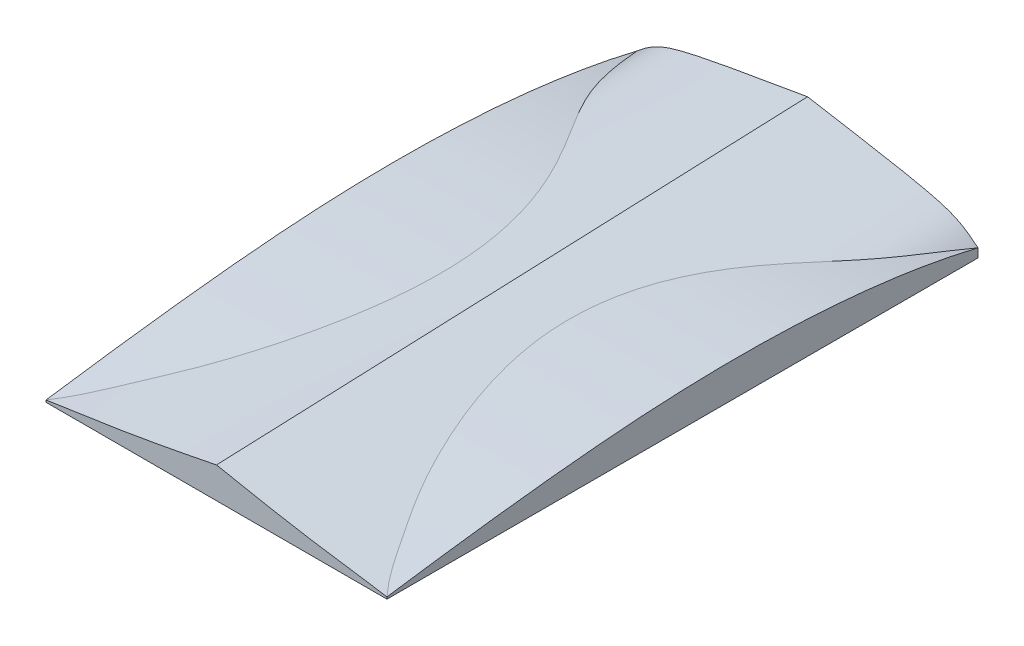
SolidWorks part; units mm, degrees
material "Custom Plastic"
ref_plane "Front Plane" through (0, 0, 0) normal (0, 0, 1) x (1, 0, 0)
ref_plane "Top Plane" through (0, 0, 0) normal (0, 1, 0) x (1, 0, 0)
ref_plane "Right Plane" through (0, 0, 0) normal (1, 0, 0) x (0, 0, -1)
sketch "Sketch1" plane through (0, 0, 0) normal (0, 1, 0) x (1, 0, 0)
  line L1 (37.5, -65) -> (-37.5, -65)
  line L2 (37.5, -65) -> (37.5, 65)
  line L3 (37.5, 65) -> (-37.5, 65)
  line L4 (-37.5, -65) -> (-37.5, 65)
  line L5 (37.5, -65) -> (-37.5, 65) construction
  line L6 (37.5, 65) -> (-37.5, -65) construction
  point P0 (0, 0)
  dimension "D1" = 130
  dimension "D2" = 75
extrude "Boss-Extrude1" add sketch "Sketch1" along normal mid plane 20
sketch "Sketch4" plane through (0, 0, 65) normal (0, 0, 1) x (1, 0, 0)
  line L3 (-37.5, -10) -> (37.5, -10)
  line L4 (-37.5, -9.5528) -> (-37.5, -10)
  line L5 (37.5, -10) -> (37.5, -9.5528)
  line L6 (-37.5, -10) -> (37.5, -10)
  line L7 (-37.5, -9.5528) -> (-37.5, -10)
  line L8 (37.5, -10) -> (37.5, -9.5528)
  spline S2 degree 3 poles (1362.5277, -2586.3983) (529.3557, 276.2334) (276.2831, 48.9391) (-12.45, -5.5894) (-15.5687, -6.1588) (-20.2581, -6.9528) (-21.823, -7.2062) (-24.9574, -7.6822) (-26.5273, -7.902) (-29.6645, -8.3595) (-31.231, -8.602) (-143.085, -25.9114) (-260.3256, 2.6626) (83.6689, -2996.3053) knots -22.671348 -22.671348 -22.671348 -22.671348 0.25 0.25 0.5 0.5 0.625 0.625 0.75 0.75 0.875 0.875 9.675339 9.675339 9.675339 9.675339 only from (0, -3.1785) to (-37.5, -9.5528)
  spline S3 degree 3 poles (-83.6298, -2996.3455) (260.326, 2.663) (143.0854, -25.9115) (31.231, -8.602) (29.6645, -8.3595) (26.5273, -7.902) (24.9573, -7.6822) (21.823, -7.2062) (20.2581, -6.9528) (15.5687, -6.1588) (12.45, -5.5894) (-276.2862, 48.9397) (-529.3639, 276.2389) (-1362.51, -2586.49) knots -8.675371 -8.675371 -8.675371 -8.675371 0.125 0.125 0.25 0.25 0.375 0.375 0.5 0.5 0.75 0.75 23.671611 23.671611 23.671611 23.671611 only from (37.5, -9.5528) to (0, -3.1785)
  spline S4 degree 3 poles (0, -3.1785) (-3.1082, -3.8038) (-6.2196, -4.4128) (-12.45, -5.5894) (-15.5687, -6.1588) (-20.2581, -6.9528) (-21.823, -7.2062) (-24.9574, -7.6822) (-26.5273, -7.902) (-29.6645, -8.3595) (-31.231, -8.602) (-34.3641, -9.0868) (-35.932, -9.32) (-37.5, -9.5528) knots 0 0 0 0 0.25 0.25 0.5 0.5 0.625 0.625 0.75 0.75 0.875 0.875 1 1 1 1
  spline S5 degree 3 poles (37.5, -9.5528) (35.932, -9.32) (34.3641, -9.0868) (31.231, -8.602) (29.6645, -8.3595) (26.5273, -7.902) (24.9573, -7.6822) (21.823, -7.2062) (20.2581, -6.9528) (15.5687, -6.1588) (12.45, -5.5894) (6.2196, -4.4128) (3.1082, -3.8038) (0, -3.1785) knots 0 0 0 0 0.125 0.125 0.25 0.25 0.375 0.375 0.5 0.5 0.75 0.75 1 1 1 1
  dimension "D1" = 0
sketch "Sketch7" plane through (0, 0, -65) normal (0, 0, -1) x (-1, 0, 0)
  line L3 (-37.5, -10) -> (37.5, -10)
  line L4 (-37.5, -8.0672) -> (-37.5, -10)
  line L5 (37.5, -10) -> (37.5, -8.0672)
  line L6 (-37.5, -10) -> (37.5, -10)
  line L7 (-37.5, -8.0672) -> (-37.5, -10)
  line L8 (37.5, -10) -> (37.5, -8.0672)
  spline S2 degree 3 poles (147.4318, 2953.7815) (446.6651, 32.4517) (214.3649, 39.1733) (-12.8775, -0.2551) (-16.0948, -0.8201) (-20.91, -1.727) (-22.5132, -2.0391) (-24.911, -2.5465) (-25.7095, -2.7224) (-27.2981, -3.0969) (-28.0886, -3.2952) (-29.6554, -3.7331) (-30.4316, -3.9729) (-31.958, -4.5286) (-32.7073, -4.8469) (-33.8, -5.4157) (-34.1598, -5.6214) (-34.8648, -6.0606) (-35.208, -6.2927) (-65.0007, -27.7231) (-40.8384, -121.4893) (-1903.7188, 2339.0086) knots -17.151311 -17.151311 -17.151311 -17.151311 0.25 0.25 0.5 0.5 0.625 0.625 0.6875 0.6875 0.75 0.75 0.8125 0.8125 0.875 0.875 0.90625 0.90625 0.9375 0.9375 3.676306 3.676306 3.676306 3.676306 only from (0, 1.9592) to (-37.5, -8.0672)
  spline S3 degree 3 poles (1650.2449, 2519.9794) (48.7593, -126.412) (64.9758, -27.7798) (34.915, -6.0803) (34.232, -5.6461) (32.7996, -4.8901) (32.0515, -4.5662) (30.8943, -4.1398) (30.5026, -4.0071) (29.718, -3.7579) (29.3242, -3.6412) (28.1393, -3.3083) (27.345, -3.1085) (25.7519, -2.732) (24.953, -2.5557) (22.5524, -2.0469) (20.9467, -1.7341) (16.124, -0.8253) (12.901, -0.2592) (-214.5163, 39.2022) (-447.698, 32.4578) (-103.9777, 2955.3101) knots -2.727115 -2.727115 -2.727115 -2.727115 0.0625 0.0625 0.125 0.125 0.1875 0.1875 0.21875 0.21875 0.25 0.25 0.3125 0.3125 0.375 0.375 0.5 0.5 0.75 0.75 18.133105 18.133105 18.133105 18.133105 only from (37.5, -8.0672) to (0, 1.9592)
  spline S4 degree 3 poles (0, 1.9592) (-3.2203, 1.4108) (-6.4405, 0.8618) (-12.8775, -0.2551) (-16.0948, -0.8201) (-20.91, -1.727) (-22.5132, -2.0391) (-24.911, -2.5465) (-25.7095, -2.7224) (-27.2981, -3.0969) (-28.0886, -3.2952) (-29.6554, -3.7331) (-30.4316, -3.9729) (-31.958, -4.5286) (-32.7073, -4.8469) (-33.8, -5.4157) (-34.1598, -5.6214) (-34.8648, -6.0606) (-35.208, -6.2927) (-36.2163, -7.018) (-36.8606, -7.5393) (-37.5, -8.0672) knots 0 0 0 0 0.25 0.25 0.5 0.5 0.625 0.625 0.6875 0.6875 0.75 0.75 0.8125 0.8125 0.875 0.875 0.90625 0.90625 0.9375 0.9375 1 1 1 1
  spline S5 degree 3 poles (37.5, -8.0672) (36.8684, -7.5457) (36.2325, -7.0314) (34.915, -6.0803) (34.232, -5.6461) (32.7996, -4.8901) (32.0515, -4.5662) (30.8943, -4.1398) (30.5026, -4.0071) (29.718, -3.7579) (29.3242, -3.6412) (28.1393, -3.3083) (27.345, -3.1085) (25.7519, -2.732) (24.953, -2.5557) (22.5524, -2.0469) (20.9467, -1.7341) (16.124, -0.8253) (12.901, -0.2592) (6.4524, 0.8598) (3.2263, 1.4098) (0, 1.9592) knots 0 0 0 0 0.0625 0.0625 0.125 0.125 0.1875 0.1875 0.21875 0.21875 0.25 0.25 0.3125 0.3125 0.375 0.375 0.5 0.5 0.75 0.75 1 1 1 1
  dimension "D1" = 0
sketch "Sketch8" plane through (0, 0, 65) normal (0, 0, 1) x (1, 0, 0)
  line L0 (37.5, -10) -> (37.5, -9.5528) construction
  line L1 (-37.5, -9.5528) -> (-37.5, -10) construction
  line L2 (-37.5, -10) -> (37.5, -10) construction
  line L3 (37.5, -10) -> (37.5, -9.5528)
  line L4 (-37.5, -9.5528) -> (-37.5, -10)
  line L5 (-37.5, -10) -> (37.5, -10)
  line L10 (-37.5, -10) -> (37.5, -10)
  line L11 (37.5, -10) -> (37.5, 10)
  line L12 (37.5, 10) -> (-37.5, 10)
  line L13 (-37.5, 10) -> (-37.5, -10)
  line L14 (-37.5, -10) -> (37.5, -10)
  line L15 (37.5, -10) -> (37.5, 10)
  line L16 (37.5, 10) -> (-37.5, 10)
  line L17 (-37.5, 10) -> (-37.5, -10)
  spline S0 degree 3 poles (25.1955, -2002.3309) (230.9447, -3.8028) (129.2143, -23.7649) (31.231, -8.602) (29.6645, -8.3595) (26.5273, -7.902) (24.9573, -7.6822) (21.823, -7.2062) (20.2581, -6.9528) (15.5687, -6.1588) (12.45, -5.5894) (-239.6477, 42.0203) (-463.9005, 220.7771) (-1069.2322, -1630.4759) knots -7.568527 -7.568527 -7.568527 -7.568527 0.125 0.125 0.25 0.25 0.375 0.375 0.5 0.5 0.75 0.75 20.731303 20.731303 20.731303 20.731303 only from (37.5, -9.5528) to (0, -3.1785) construction
  spline S1 degree 3 poles (1069.2512, -1630.4468) (463.8959, 220.7748) (239.6463, 42.0201) (-12.45, -5.5894) (-15.5687, -6.1588) (-20.2581, -6.9528) (-21.823, -7.2062) (-24.9574, -7.6822) (-26.5273, -7.902) (-29.6645, -8.3595) (-31.231, -8.602) (-129.2137, -23.7648) (-230.9439, -3.8031) (-25.1705, -2002.2918) knots -19.731182 -19.731182 -19.731182 -19.731182 0.25 0.25 0.5 0.5 0.625 0.625 0.75 0.75 0.875 0.875 8.568483 8.568483 8.568483 8.568483 only from (0, -3.1785) to (-37.5, -9.5528) construction
  spline S2 degree 3 poles (37.5, -9.5528) (35.932, -9.32) (34.3641, -9.0868) (31.231, -8.602) (29.6645, -8.3595) (26.5273, -7.902) (24.9573, -7.6822) (21.823, -7.2062) (20.2581, -6.9528) (15.5687, -6.1588) (12.45, -5.5894) (6.2196, -4.4128) (3.1082, -3.8038) (0, -3.1785) knots 0 0 0 0 0.125 0.125 0.25 0.25 0.375 0.375 0.5 0.5 0.75 0.75 1 1 1 1
  spline S3 degree 3 poles (0, -3.1785) (-3.1082, -3.8038) (-6.2196, -4.4128) (-12.45, -5.5894) (-15.5687, -6.1588) (-20.2581, -6.9528) (-21.823, -7.2062) (-24.9574, -7.6822) (-26.5273, -7.902) (-29.6645, -8.3595) (-31.231, -8.602) (-34.3641, -9.0868) (-35.932, -9.32) (-37.5, -9.5528) knots 0 0 0 0 0.25 0.25 0.5 0.5 0.625 0.625 0.75 0.75 0.875 0.875 1 1 1 1
  dimension "D1" = 0
sketch "Sketch14" plane through (37.5, 0, 0) normal (1, 0, 0) x (0, 0, -1)
  line L4 (-65, -10) -> (65, -10)
  line L5 (65, -10) -> (65, 10)
  line L6 (65, 10) -> (-65, 10)
  line L7 (-65, 10) -> (-65, -10)
  line L8 (-65, -10) -> (65, -10)
  line L9 (65, -10) -> (65, 10)
  line L10 (65, 10) -> (-65, 10)
  line L11 (-65, 10) -> (-65, -10)
  spline S0 degree 3 poles (302.1115, -1979.9432) (336.8552, -226.6773) (202.4863, -27.6201) (43.5369, -4.1805) (38.1282, -3.6036) (27.2724, -2.8022) (21.8255, -2.5767) (13.6304, -2.4646) (10.8947, -2.4652) (5.4345, -2.5372) (2.7076, -2.6082) (-5.4642, -2.9203) (-10.8999, -3.2637) (-21.7529, -4.155) (-27.1705, -4.699) (-37.9947, -5.9114) (-43.4009, -6.5821) (-337.0021, -45.3581) (-614.0336, -207.5109) (-1071.7834, 1638.4672) knots -3.439572 -3.439572 -3.439572 -3.439572 0.125 0.125 0.25 0.25 0.375 0.375 0.4375 0.4375 0.5 0.5 0.625 0.625 0.75 0.75 0.875 0.875 7.543306 7.543306 7.543306 7.543306 only from (65, -8.0672) to (-65, -9.5528) construction
  spline S1 degree 3 poles (65, -8.0672) (59.6686, -6.7798) (54.3071, -5.7688) (43.5369, -4.1805) (38.1282, -3.6036) (27.2724, -2.8022) (21.8255, -2.5767) (13.6304, -2.4646) (10.8947, -2.4652) (5.4345, -2.5372) (2.7076, -2.6082) (-5.4642, -2.9203) (-10.8999, -3.2637) (-21.7529, -4.155) (-27.1705, -4.699) (-37.9947, -5.9114) (-43.4009, -6.5821) (-54.2057, -8.0091) (-59.6042, -8.7662) (-65, -9.5528) knots 0 0 0 0 0.125 0.125 0.25 0.25 0.375 0.375 0.4375 0.4375 0.5 0.5 0.625 0.625 0.75 0.75 0.875 0.875 1 1 1 1
  dimension "D1" = 0
sketch "Sketch15" plane through (-37.5, 0, 0) normal (-1, 0, 0) x (0, 0, 1)
  line L0 (65, -10) -> (-65, -10) construction
  line L1 (65, -10) -> (-65, -10)
  line L2 (-65, -8.0672) -> (-65, -10)
  line L3 (65, -9.5528) -> (65, -10)
  spline S0 degree 3 poles (-302.1115, -1979.9432) (-336.8552, -226.6773) (-202.4863, -27.6201) (-43.5369, -4.1805) (-38.1282, -3.6036) (-27.2724, -2.8022) (-21.8255, -2.5767) (-13.6304, -2.4646) (-10.8947, -2.4652) (-5.4345, -2.5372) (-2.7076, -2.6082) (5.4642, -2.9203) (10.8999, -3.2637) (21.7529, -4.155) (27.1705, -4.699) (37.9947, -5.9114) (43.4009, -6.5821) (337.0021, -45.3581) (614.0336, -207.5109) (1071.7834, 1638.4672) knots -3.439572 -3.439572 -3.439572 -3.439572 0.125 0.125 0.25 0.25 0.375 0.375 0.4375 0.4375 0.5 0.5 0.625 0.625 0.75 0.75 0.875 0.875 7.543306 7.543306 7.543306 7.543306 only from (-65, -8.0672) to (65, -9.5528) construction
  spline S1 degree 3 poles (-65, -8.0672) (-59.6686, -6.7798) (-54.3071, -5.7688) (-43.5369, -4.1805) (-38.1282, -3.6036) (-27.2724, -2.8022) (-21.8255, -2.5767) (-13.6304, -2.4646) (-10.8947, -2.4652) (-5.4345, -2.5372) (-2.7076, -2.6082) (5.4642, -2.9203) (10.8999, -3.2637) (21.7529, -4.155) (27.1705, -4.699) (37.9947, -5.9114) (43.4009, -6.5821) (54.2057, -8.0091) (59.6042, -8.7662) (65, -9.5528) knots 0 0 0 0 0.125 0.125 0.25 0.25 0.375 0.375 0.4375 0.4375 0.5 0.5 0.625 0.625 0.75 0.75 0.875 0.875 1 1 1 1
sketch "Sketch16" plane through (37.5, 0, 0) normal (1, 0, 0) x (0, 0, -1)
  line L0 (-65, -10) -> (65, -10) construction
  line L1 (-65, -10) -> (65, -10)
  line L2 (-65, -9.5528) -> (-65, -10)
  line L3 (65, -8.0672) -> (65, -10)
  spline S0 degree 3 poles (302.1115, -1979.9432) (336.8552, -226.6773) (202.4863, -27.6201) (43.5369, -4.1805) (38.1282, -3.6036) (27.2724, -2.8022) (21.8255, -2.5767) (13.6304, -2.4646) (10.8947, -2.4652) (5.4345, -2.5372) (2.7076, -2.6082) (-5.4642, -2.9203) (-10.8999, -3.2637) (-21.7529, -4.155) (-27.1705, -4.699) (-37.9947, -5.9114) (-43.4009, -6.5821) (-337.0021, -45.3581) (-614.0336, -207.5109) (-1071.7834, 1638.4672) knots -3.439572 -3.439572 -3.439572 -3.439572 0.125 0.125 0.25 0.25 0.375 0.375 0.4375 0.4375 0.5 0.5 0.625 0.625 0.75 0.75 0.875 0.875 7.543306 7.543306 7.543306 7.543306 only from (65, -8.0672) to (-65, -9.5528) construction
  spline S1 degree 3 poles (65, -8.0672) (59.6686, -6.7798) (54.3071, -5.7688) (43.5369, -4.1805) (38.1282, -3.6036) (27.2724, -2.8022) (21.8255, -2.5767) (13.6304, -2.4646) (10.8947, -2.4652) (5.4345, -2.5372) (2.7076, -2.6082) (-5.4642, -2.9203) (-10.8999, -3.2637) (-21.7529, -4.155) (-27.1705, -4.699) (-37.9947, -5.9114) (-43.4009, -6.5821) (-54.2057, -8.0091) (-59.6042, -8.7662) (-65, -9.5528) knots 0 0 0 0 0.125 0.125 0.25 0.25 0.375 0.375 0.4375 0.4375 0.5 0.5 0.625 0.625 0.75 0.75 0.875 0.875 1 1 1 1
sketch "Sketch17" plane through (0, 0, -65) normal (0, 0, -1) x (-1, 0, 0)
  line L0 (37.5, -10) -> (37.5, -8.0672) construction
  line L1 (-37.5, -10) -> (37.5, -10) construction
  line L2 (-37.5, -8.0672) -> (-37.5, -10) construction
  line L3 (37.5, -10) -> (37.5, -8.0672)
  line L4 (-37.5, -10) -> (37.5, -10)
  line L5 (-37.5, -8.0672) -> (-37.5, -10)
  spline S0 degree 3 poles (1131.1538, 1665.3044) (52.0496, -103.3935) (61.3715, -25.178) (34.915, -6.0803) (34.232, -5.6461) (32.7996, -4.8901) (32.0515, -4.5662) (30.8943, -4.1398) (30.5026, -4.0071) (29.718, -3.7579) (29.3242, -3.6412) (28.1393, -3.3083) (27.345, -3.1085) (25.7519, -2.732) (24.953, -2.5557) (22.5524, -2.0469) (20.9467, -1.7341) (16.124, -0.8253) (12.901, -0.2592) (-185.493, 34.1661) (-387.4749, 33.439) (-209.7345, 1960.999) knots -2.38515 -2.38515 -2.38515 -2.38515 0.0625 0.0625 0.125 0.125 0.1875 0.1875 0.21875 0.21875 0.25 0.25 0.3125 0.3125 0.375 0.375 0.5 0.5 0.75 0.75 15.882747 15.882747 15.882747 15.882747 only from (37.5, -8.0672) to (0, 1.9592) construction
  spline S1 degree 3 poles (238.2487, 1957.9567) (386.5167, 33.4284) (185.295, 34.1294) (-12.8775, -0.2551) (-16.0948, -0.8201) (-20.91, -1.727) (-22.5132, -2.0391) (-24.911, -2.5465) (-25.7095, -2.7224) (-27.2981, -3.0969) (-28.0886, -3.2952) (-29.6554, -3.7331) (-30.4316, -3.9729) (-31.958, -4.5286) (-32.7073, -4.8469) (-33.8, -5.4157) (-34.1598, -5.6214) (-34.8648, -6.0606) (-35.208, -6.2927) (-61.381, -25.1194) (-45.9671, -99.5405) (-1298.8469, 1542.7761) knots -14.893272 -14.893272 -14.893272 -14.893272 0.25 0.25 0.5 0.5 0.625 0.625 0.6875 0.6875 0.75 0.75 0.8125 0.8125 0.875 0.875 0.90625 0.90625 0.9375 0.9375 3.339749 3.339749 3.339749 3.339749 only from (0, 1.9592) to (-37.5, -8.0672) construction
  spline S2 degree 3 poles (37.5, -8.0672) (36.8684, -7.5457) (36.2325, -7.0314) (34.915, -6.0803) (34.232, -5.6461) (32.7996, -4.8901) (32.0515, -4.5662) (30.8943, -4.1398) (30.5026, -4.0071) (29.718, -3.7579) (29.3242, -3.6412) (28.1393, -3.3083) (27.345, -3.1085) (25.7519, -2.732) (24.953, -2.5557) (22.5524, -2.0469) (20.9467, -1.7341) (16.124, -0.8253) (12.901, -0.2592) (6.4524, 0.8598) (3.2263, 1.4098) (0, 1.9592) knots 0 0 0 0 0.0625 0.0625 0.125 0.125 0.1875 0.1875 0.21875 0.21875 0.25 0.25 0.3125 0.3125 0.375 0.375 0.5 0.5 0.75 0.75 1 1 1 1
  spline S3 degree 3 poles (0, 1.9592) (-3.2203, 1.4108) (-6.4405, 0.8618) (-12.8775, -0.2551) (-16.0948, -0.8201) (-20.91, -1.727) (-22.5132, -2.0391) (-24.911, -2.5465) (-25.7095, -2.7224) (-27.2981, -3.0969) (-28.0886, -3.2952) (-29.6554, -3.7331) (-30.4316, -3.9729) (-31.958, -4.5286) (-32.7073, -4.8469) (-33.8, -5.4157) (-34.1598, -5.6214) (-34.8648, -6.0606) (-35.208, -6.2927) (-36.2163, -7.018) (-36.8606, -7.5393) (-37.5, -8.0672) knots 0 0 0 0 0.25 0.25 0.5 0.5 0.625 0.625 0.6875 0.6875 0.75 0.75 0.8125 0.8125 0.875 0.875 0.90625 0.90625 0.9375 0.9375 1 1 1 1
sketch "Sketch18" plane through (0, 0, -65) normal (0, 0, -1) x (-1, 0, 0)
  line L0 (-37.5, -8.0672) -> (-37.5, 10)
  line L1 (-37.5, 10) -> (37.5, 10)
  line L2 (37.5, 10) -> (37.5, -8.0672)
  spline S0 degree 3 poles (1131.1538, 1665.3044) (52.0496, -103.3935) (61.3715, -25.178) (34.915, -6.0803) (34.232, -5.6461) (32.7996, -4.8901) (32.0515, -4.5662) (30.8943, -4.1398) (30.5026, -4.0071) (29.718, -3.7579) (29.3242, -3.6412) (28.1393, -3.3083) (27.345, -3.1085) (25.7519, -2.732) (24.953, -2.5557) (22.5524, -2.0469) (20.9467, -1.7341) (16.124, -0.8253) (12.901, -0.2592) (-185.493, 34.1661) (-387.4749, 33.439) (-209.7345, 1960.999) knots -2.38515 -2.38515 -2.38515 -2.38515 0.0625 0.0625 0.125 0.125 0.1875 0.1875 0.21875 0.21875 0.25 0.25 0.3125 0.3125 0.375 0.375 0.5 0.5 0.75 0.75 15.882747 15.882747 15.882747 15.882747 only from (37.5, -8.0672) to (0, 1.9592) construction
  spline S1 degree 3 poles (238.2487, 1957.9567) (386.5167, 33.4284) (185.295, 34.1294) (-12.8775, -0.2551) (-16.0948, -0.8201) (-20.91, -1.727) (-22.5132, -2.0391) (-24.911, -2.5465) (-25.7095, -2.7224) (-27.2981, -3.0969) (-28.0886, -3.2952) (-29.6554, -3.7331) (-30.4316, -3.9729) (-31.958, -4.5286) (-32.7073, -4.8469) (-33.8, -5.4157) (-34.1598, -5.6214) (-34.8648, -6.0606) (-35.208, -6.2927) (-61.381, -25.1194) (-45.9671, -99.5405) (-1298.8469, 1542.7761) knots -14.893272 -14.893272 -14.893272 -14.893272 0.25 0.25 0.5 0.5 0.625 0.625 0.6875 0.6875 0.75 0.75 0.8125 0.8125 0.875 0.875 0.90625 0.90625 0.9375 0.9375 3.339749 3.339749 3.339749 3.339749 only from (0, 1.9592) to (-37.5, -8.0672) construction
  spline S2 degree 3 poles (37.5, -8.0672) (36.8684, -7.5457) (36.2325, -7.0314) (34.915, -6.0803) (34.232, -5.6461) (32.7996, -4.8901) (32.0515, -4.5662) (30.8943, -4.1398) (30.5026, -4.0071) (29.718, -3.7579) (29.3242, -3.6412) (28.1393, -3.3083) (27.345, -3.1085) (25.7519, -2.732) (24.953, -2.5557) (22.5524, -2.0469) (20.9467, -1.7341) (16.124, -0.8253) (12.901, -0.2592) (6.4524, 0.8598) (3.2263, 1.4098) (0, 1.9592) knots 0 0 0 0 0.0625 0.0625 0.125 0.125 0.1875 0.1875 0.21875 0.21875 0.25 0.25 0.3125 0.3125 0.375 0.375 0.5 0.5 0.75 0.75 1 1 1 1
  spline S3 degree 3 poles (0, 1.9592) (-3.2203, 1.4108) (-6.4405, 0.8618) (-12.8775, -0.2551) (-16.0948, -0.8201) (-20.91, -1.727) (-22.5132, -2.0391) (-24.911, -2.5465) (-25.7095, -2.7224) (-27.2981, -3.0969) (-28.0886, -3.2952) (-29.6554, -3.7331) (-30.4316, -3.9729) (-31.958, -4.5286) (-32.7073, -4.8469) (-33.8, -5.4157) (-34.1598, -5.6214) (-34.8648, -6.0606) (-35.208, -6.2927) (-36.2163, -7.018) (-36.8606, -7.5393) (-37.5, -8.0672) knots 0 0 0 0 0.25 0.25 0.5 0.5 0.625 0.625 0.6875 0.6875 0.75 0.75 0.8125 0.8125 0.875 0.875 0.90625 0.90625 0.9375 0.9375 1 1 1 1
sketch "Sketch19" plane through (0, 0, 65) normal (0, 0, 1) x (1, 0, 0)
  line L0 (-37.5, -9.5528) -> (-37.5, 10)
  line L1 (-37.5, 10) -> (37.5, 10)
  line L2 (37.5, 10) -> (37.5, -9.5528)
  spline S0 degree 3 poles (25.1955, -2002.3309) (230.9447, -3.8028) (129.2143, -23.7649) (31.231, -8.602) (29.6645, -8.3595) (26.5273, -7.902) (24.9573, -7.6822) (21.823, -7.2062) (20.2581, -6.9528) (15.5687, -6.1588) (12.45, -5.5894) (-239.6477, 42.0203) (-463.9005, 220.7771) (-1069.2322, -1630.4759) knots -7.568527 -7.568527 -7.568527 -7.568527 0.125 0.125 0.25 0.25 0.375 0.375 0.5 0.5 0.75 0.75 20.731303 20.731303 20.731303 20.731303 only from (37.5, -9.5528) to (0, -3.1785) construction
  spline S1 degree 3 poles (1069.2512, -1630.4468) (463.8959, 220.7748) (239.6463, 42.0201) (-12.45, -5.5894) (-15.5687, -6.1588) (-20.2581, -6.9528) (-21.823, -7.2062) (-24.9574, -7.6822) (-26.5273, -7.902) (-29.6645, -8.3595) (-31.231, -8.602) (-129.2137, -23.7648) (-230.9439, -3.8031) (-25.1705, -2002.2918) knots -19.731182 -19.731182 -19.731182 -19.731182 0.25 0.25 0.5 0.5 0.625 0.625 0.75 0.75 0.875 0.875 8.568483 8.568483 8.568483 8.568483 only from (0, -3.1785) to (-37.5, -9.5528) construction
  spline S2 degree 3 poles (37.5, -9.5528) (35.932, -9.32) (34.3641, -9.0868) (31.231, -8.602) (29.6645, -8.3595) (26.5273, -7.902) (24.9573, -7.6822) (21.823, -7.2062) (20.2581, -6.9528) (15.5687, -6.1588) (12.45, -5.5894) (6.2196, -4.4128) (3.1082, -3.8038) (0, -3.1785) knots 0 0 0 0 0.125 0.125 0.25 0.25 0.375 0.375 0.5 0.5 0.75 0.75 1 1 1 1
  spline S3 degree 3 poles (0, -3.1785) (-3.1082, -3.8038) (-6.2196, -4.4128) (-12.45, -5.5894) (-15.5687, -6.1588) (-20.2581, -6.9528) (-21.823, -7.2062) (-24.9574, -7.6822) (-26.5273, -7.902) (-29.6645, -8.3595) (-31.231, -8.602) (-34.3641, -9.0868) (-35.932, -9.32) (-37.5, -9.5528) knots 0 0 0 0 0.25 0.25 0.5 0.5 0.625 0.625 0.75 0.75 0.875 0.875 1 1 1 1
sketch "Sketch21" plane through (-37.5, 0, 0) normal (-1, 0, 0) x (0, 0, 1)
  line L3 (-65, -8.0672) -> (-65, -10)
  line L4 (-65, -10) -> (65, -10)
  line L5 (65, -10) -> (65, -9.5528)
  spline S0 degree 3 poles (-302.1115, -1979.9432) (-336.8552, -226.6773) (-202.4863, -27.6201) (-43.5369, -4.1805) (-38.1282, -3.6036) (-27.2724, -2.8022) (-21.8255, -2.5767) (-13.6304, -2.4646) (-10.8947, -2.4652) (-5.4345, -2.5372) (-2.7076, -2.6082) (5.4642, -2.9203) (10.8999, -3.2637) (21.7529, -4.155) (27.1705, -4.699) (37.9947, -5.9114) (43.4009, -6.5821) (337.0021, -45.3581) (614.0336, -207.5109) (1071.7834, 1638.4672) knots -3.439572 -3.439572 -3.439572 -3.439572 0.125 0.125 0.25 0.25 0.375 0.375 0.4375 0.4375 0.5 0.5 0.625 0.625 0.75 0.75 0.875 0.875 7.543306 7.543306 7.543306 7.543306 only from (-65, -8.0672) to (65, -9.5528) construction
  spline S1 degree 3 poles (-65, -8.0672) (-59.6686, -6.7798) (-54.3071, -5.7688) (-43.5369, -4.1805) (-38.1282, -3.6036) (-27.2724, -2.8022) (-21.8255, -2.5767) (-13.6304, -2.4646) (-10.8947, -2.4652) (-5.4345, -2.5372) (-2.7076, -2.6082) (5.4642, -2.9203) (10.8999, -3.2637) (21.7529, -4.155) (27.1705, -4.699) (37.9947, -5.9114) (43.4009, -6.5821) (54.2057, -8.0091) (59.6042, -8.7662) (65, -9.5528) knots 0 0 0 0 0.125 0.125 0.25 0.25 0.375 0.375 0.4375 0.4375 0.5 0.5 0.625 0.625 0.75 0.75 0.875 0.875 1 1 1 1
sketch "Sketch22" plane through (37.5, 0, 0) normal (1, 0, 0) x (0, 0, -1)
  line L6 (-65, -9.5528) -> (-65, -10)
  line L7 (-65, -10) -> (65, -10)
  line L8 (-65, -10) -> (65, -10) construction
  line L9 (65, -10) -> (65, -8.0672)
  spline S0 degree 3 poles (302.1115, -1979.9432) (336.8552, -226.6773) (202.4863, -27.6201) (43.5369, -4.1805) (38.1282, -3.6036) (27.2724, -2.8022) (21.8255, -2.5767) (13.6304, -2.4646) (10.8947, -2.4652) (5.4345, -2.5372) (2.7076, -2.6082) (-5.4642, -2.9203) (-10.8999, -3.2637) (-21.7529, -4.155) (-27.1705, -4.699) (-37.9947, -5.9114) (-43.4009, -6.5821) (-337.0021, -45.3581) (-614.0336, -207.5109) (-1071.7834, 1638.4672) knots -3.439572 -3.439572 -3.439572 -3.439572 0.125 0.125 0.25 0.25 0.375 0.375 0.4375 0.4375 0.5 0.5 0.625 0.625 0.75 0.75 0.875 0.875 7.543306 7.543306 7.543306 7.543306 only from (65, -8.0672) to (-65, -9.5528) construction
  spline S1 degree 3 poles (65, -8.0672) (59.6686, -6.7798) (54.3071, -5.7688) (43.5369, -4.1805) (38.1282, -3.6036) (27.2724, -2.8022) (21.8255, -2.5767) (13.6304, -2.4646) (10.8947, -2.4652) (5.4345, -2.5372) (2.7076, -2.6082) (-5.4642, -2.9203) (-10.8999, -3.2637) (-21.7529, -4.155) (-27.1705, -4.699) (-37.9947, -5.9114) (-43.4009, -6.5821) (-54.2057, -8.0091) (-59.6042, -8.7662) (-65, -9.5528) knots 0 0 0 0 0.125 0.125 0.25 0.25 0.375 0.375 0.4375 0.4375 0.5 0.5 0.625 0.625 0.75 0.75 0.875 0.875 1 1 1 1
loft "Cut-Loft2" cut profiles "Sketch18", "Sketch19"
loft "Loft1" add profiles "Sketch22", "Sketch21"
